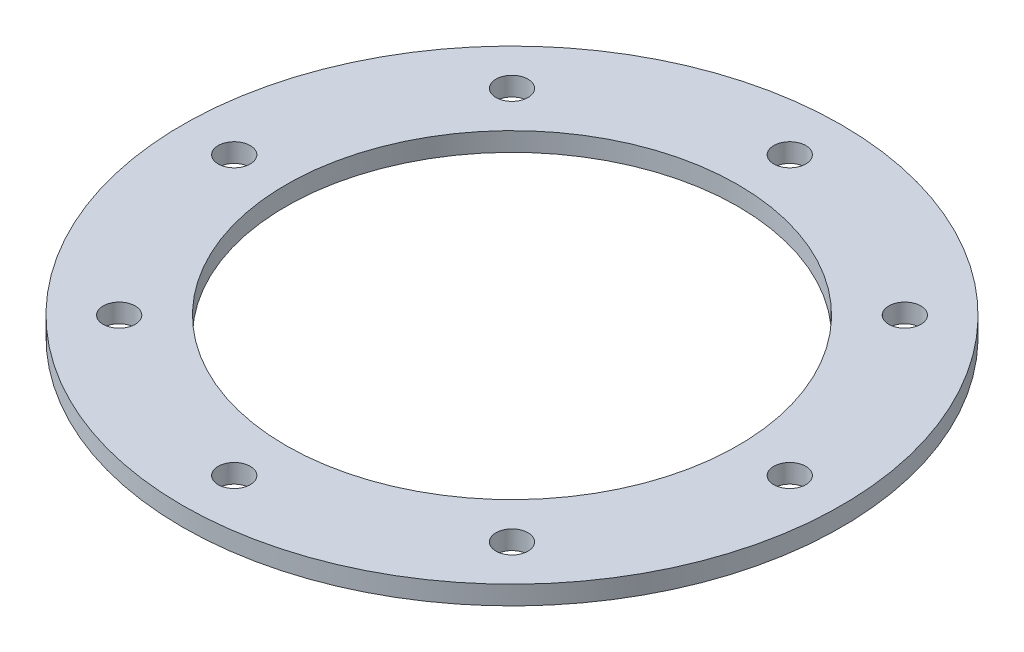
SolidWorks part; units mm, degrees
material "AISI 304"
ref_plane "Спереди" through (0, 0, 0) normal (0, 0, 1) x (1, 0, 0)
ref_plane "Сверху" through (0, 0, 0) normal (0, 1, 0) x (1, 0, 0)
ref_plane "Справа" through (0, 0, 0) normal (1, 0, 0) x (0, 0, -1)
sketch "Эскиз1" plane through (0, 0, 0) normal (0, 1, 0) x (1, 0, 0)
  line L0 (0, 0) -> (59, 0) construction
  circle A0 centre (0, 0) radius 70
  circle A1 centre (0, 0) radius 48
  circle A2 centre (0, 0) radius 59 construction
  circle A3 centre (59, 0) radius 3.4
  circle A4 centre (41.7193, -41.7193) radius 3.4
  circle A5 centre (0, -59) radius 3.4
  circle A6 centre (-41.7193, -41.7193) radius 3.4
  circle A7 centre (-59, 0) radius 3.4
  circle A8 centre (-41.7193, 41.7193) radius 3.4
  circle A9 centre (0, 59) radius 3.4
  circle A10 centre (41.7193, 41.7193) radius 3.4
  dimension "D1" = 140
  dimension "D2" = 96
  dimension "D3" = 118
  dimension "D4" = 6.8
  dimension "D5" = 8
extrude "Бобышка-Вытянуть1" add sketch "Эскиз1" along normal blind 4
